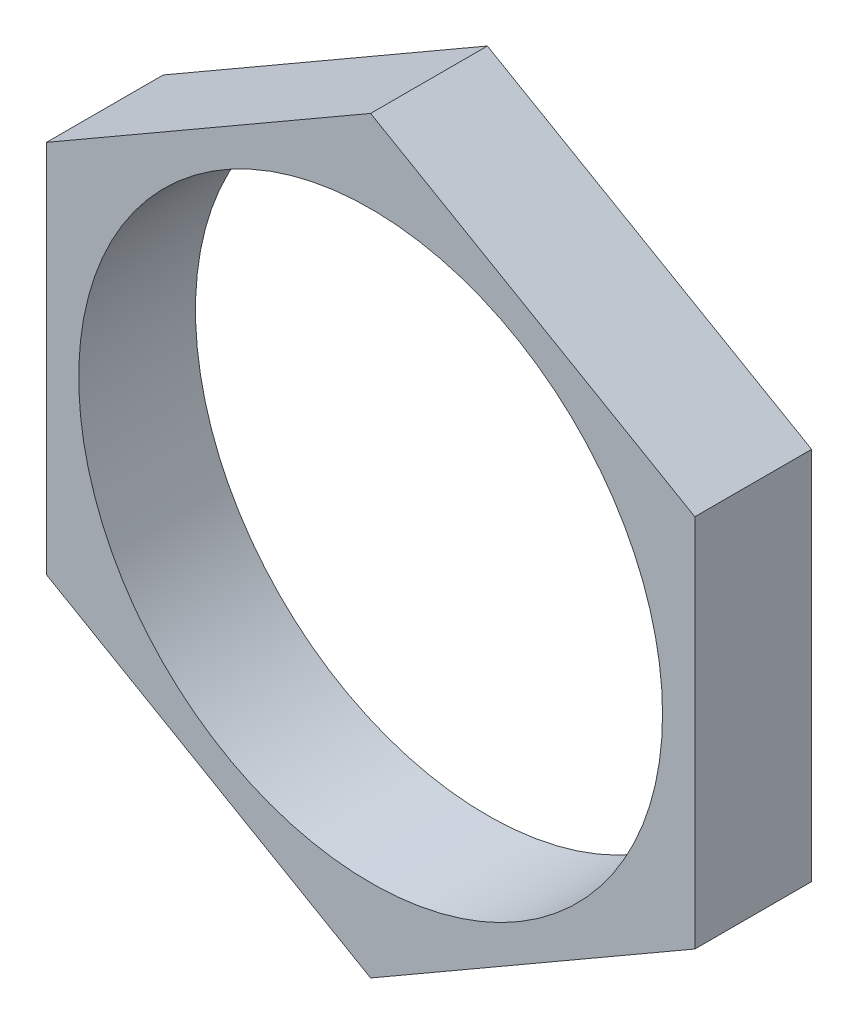
SolidWorks part; units mm, degrees
ref_plane "Front Plane" through (0, 0, 0) normal (0, 0, 1) x (1, 0, 0)
ref_plane "Top Plane" through (0, 0, 0) normal (0, 1, 0) x (1, 0, 0)
ref_plane "Right Plane" through (0, 0, 0) normal (1, 0, 0) x (0, 0, -1)
sketch "Sketch1" plane through (0, 0, 0) normal (0, 0, 1) x (1, 0, 0)
  line L1 (0, 12.8244) -> (-11.1063, 6.4122)
  line L2 (-11.1063, 6.4122) -> (-11.1063, -6.4122)
  line L3 (-11.1063, -6.4122) -> (0, -12.8244)
  line L4 (0, -12.8244) -> (11.1063, -6.4122)
  line L5 (11.1063, -6.4122) -> (11.1063, 6.4122)
  line L6 (11.1063, 6.4122) -> (0, 12.8244)
  circle A0 centre (0, 0) radius 10
  circle A1 centre (0, 0) radius 11.1063 construction
extrude "Boss-Extrude1" add sketch "Sketch1" along normal blind 4
